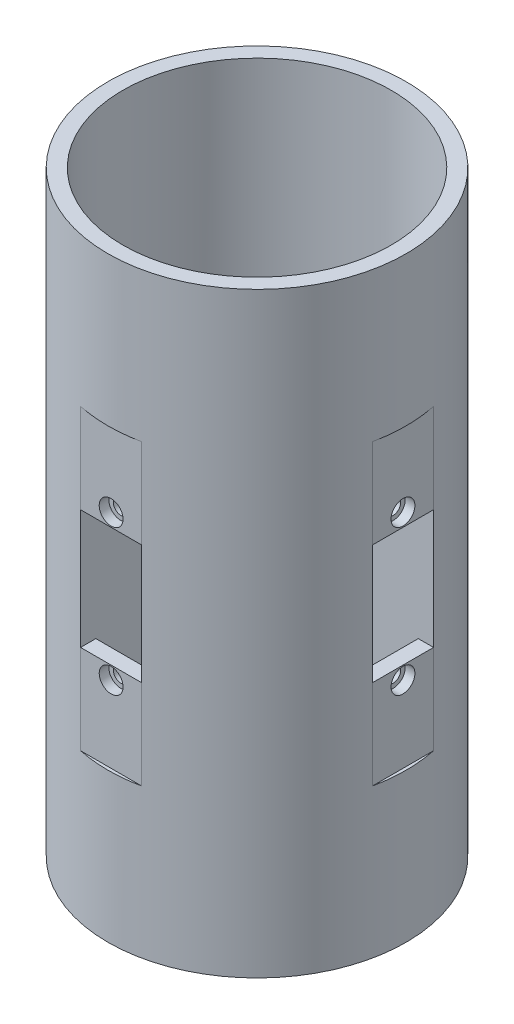
SolidWorks part; units mm, degrees
ref_plane "前视基准面" through (0, 0, 0) normal (0, 0, 1) x (1, 0, 0)
ref_plane "上视基准面" through (0, 0, 0) normal (0, 1, 0) x (1, 0, 0)
ref_plane "右视基准面" through (0, 0, 0) normal (1, 0, 0) x (0, 0, -1)
other "Configuration Table"
sketch "草图1" plane through (0, 0, 0) normal (0, 1, 0) x (1, 0, 0)
  circle A0 centre (0, 0) radius 20
  circle A1 centre (0, 0) radius 18
  dimension "D1" = 40
  dimension "D2" = 36
extrude "凸台-拉伸1" add sketch "草图1" along normal blind 80
sketch "草图2" plane through (0, 0, 0) normal (0, 1, 0) x (1, 0, 0)
  line L0 (-1000, 0) -> (49000, 0) construction
  line L1 (0, -1000) -> (0, 49000) construction
  line L2 (17.5268, -4.1) -> (17.5268, 4.1)
  line L3 (17.5268, 4.1) -> (-17.5268, 4.1) construction
  line L4 (17.5268, -4.1) -> (-17.5268, -4.1) construction
  line L5 (19.5752, 4.1) -> (19.5752, -4.1)
  line L6 (-17.5268, 4.1) -> (-17.5268, -4.1)
  line L7 (-19.5752, 4.1) -> (-19.5752, -4.1)
  line L8 (17.5268, 4.1) -> (19.5752, 4.1)
  line L9 (19.5752, -4.1) -> (17.5268, -4.1)
  line L10 (-19.5752, 4.1) -> (-17.5268, 4.1)
  line L11 (-17.5268, -4.1) -> (-19.5752, -4.1)
  line L12 (-707.1068, -707.1068) -> (34648.2323, 34648.2323) construction
  line L13 (707.1068, -707.1068) -> (-34648.2323, 34648.2323) construction
  line L14 (-4.1, -17.5268) -> (-4.1, -19.5752)
  line L15 (-4.1, -19.5752) -> (4.1, -19.5752)
  line L16 (4.1, -17.5268) -> (-4.1, -17.5268)
  line L17 (4.1, -19.5752) -> (4.1, -17.5268)
  line L18 (-4.1, 19.5752) -> (-4.1, 17.5268)
  line L19 (-4.1, 19.5752) -> (4.1, 19.5752)
  line L20 (4.1, 17.5268) -> (4.1, 19.5752)
  line L21 (-4.1, 17.5268) -> (4.1, 17.5268)
  circle A0 centre (0, 0) radius 18
  circle A1 centre (0, 0) radius 20
  point P11 (17.5268, 0)
  dimension "D1" = 36
  dimension "D2" = 40
  dimension "D3" = 8.2
  dimension "D4" = 8.2
  dimension "D5" = 8.2
extrude "凸台-拉伸2" add sketch "草图2" along normal blind 30 from offset 25 contours A0 L20 L19 L18 | L15 L17 L16 L14 | L7 L11 L6 L10 | L9 L2 L8 L5
sketch "草图3" plane through (0, 0, 0) normal (0, 1, 0) x (1, 0, 0)
  line L0 (-4.1, 19.5752) -> (4.1, 19.5752) construction
  line L1 (-4.1, 19.5752) -> (4.1, 19.5752)
  line L2 (-4.1, -19.5752) -> (4.1, -19.5752) construction
  line L3 (19.5752, 4.1) -> (19.5752, -4.1) construction
  line L4 (-19.5752, 4.1) -> (-19.5752, -4.1) construction
  line L5 (-4.1, -19.5752) -> (4.1, -19.5752)
  line L6 (19.5752, 4.1) -> (19.5752, -4.1)
  line L7 (-19.5752, 4.1) -> (-19.5752, -4.1)
  circle A0 centre (0, 0) radius 20 construction
  circle A1 centre (0, 0) radius 20
extrude "切除-拉伸1" cut sketch "草图3" along normal blind 40 from offset 20 contours L7 A1 | L5 A1 | L6 A1 | L1 A1
sketch "草图4" plane through (0, 0, 0) normal (0, 0, 1) x (1, 0, 0)
  line L0 (4.1, 28.5) -> (4.1, 51.5)
  line L1 (-4.1, 28.5) -> (-4.1, 51.5)
  line L2 (-4.1, 51.5) -> (4.1, 51.5)
  line L3 (4.1, 28.5) -> (-4.1, 28.5)
  line L4 (-4.1, 20) -> (4.1, 20)
  line L5 (4.1, 20) -> (4.1, 60)
  line L6 (4.1, 60) -> (-4.1, 60)
  line L7 (-4.1, 60) -> (-4.1, 20)
  line L8 (-4.1, 20) -> (4.1, 20) construction
  line L9 (4.1, 20) -> (4.1, 60) construction
  line L10 (4.1, 60) -> (-4.1, 60) construction
  line L11 (-4.1, 60) -> (-4.1, 20) construction
  line L12 (4.1, 51.5) -> (-4.1, 28.5) construction
  line L13 (-4.1, 51.5) -> (4.1, 28.5) construction
  line L14 (0, 49.75) -> (0, 30.25) construction
  line L15 (4.1, 32) -> (4.1, 48)
  line L16 (4.1, 48) -> (-4.1, 48)
  line L17 (4.1, 32) -> (-4.1, 32)
  line L18 (-4.1, 32) -> (-4.1, 48)
  circle A0 centre (0, 49.75) radius 1
  circle A1 centre (0, 30.25) radius 1
  point P7 (4.1, 40)
  point P10 (-4.1, 40)
  point P13 (0, 40)
  point P18 (4.1, 40)
  dimension "D5" = 2
  dimension "D6" = 2
  dimension "D2" = 23
  dimension "D3" = 23
  dimension "D4" = 19.5
  dimension "D1" = 0
extrude "切除-拉伸3" cut sketch "草图4" against normal blind 30 and the other way blind 30 contours L17 L0 L16 L1 | A0 | A1
sketch "草图5" plane through (0, 0, 0) normal (1, 0, 0) x (0, 0, -1)
  line L4 (4.1, 60) -> (-4.1, 20) construction
  line L5 (-4.1, 20) -> (4.1, 20) construction
  line L6 (4.1, 20) -> (-4.1, 60) construction
  line L7 (4.1, 32) -> (4.1, 48)
  line L8 (-4.1, 20) -> (4.1, 20)
  line L9 (4.1, 20) -> (4.1, 60)
  line L10 (4.1, 60) -> (-4.1, 60)
  line L11 (-4.1, 60) -> (-4.1, 20)
  line L12 (-4.1, 20) -> (4.1, 20) construction
  line L13 (4.1, 20) -> (4.1, 60) construction
  line L14 (4.1, 60) -> (-4.1, 60) construction
  line L15 (-4.1, 60) -> (-4.1, 20) construction
  line L16 (4.1, 48) -> (-4.1, 48)
  line L17 (-4.1, 48) -> (-4.1, 32)
  line L18 (-4.1, 32) -> (4.1, 32)
  line L19 (0, 49.75) -> (0, 30.25) construction
  circle A0 centre (0, 49.75) radius 1
  circle A1 centre (0, 30.25) radius 1
  point P5 (4.1, 40)
  point P13 (0, 40)
  dimension "D4" = 2
  dimension "D5" = 2
  dimension "D2" = 16
  dimension "D3" = 19.5
  dimension "D1" = 0
extrude "切除-拉伸4" cut sketch "草图5" against normal blind 30 and the other way blind 30 contours A0 | L18 L7 L16 L17 | A1
sketch "草图6" plane through (0, 0, 0) normal (0, 1, 0) x (1, 0, 0)
  line L0 (17.5268, -4.1) -> (17.5268, 4.1) construction
  line L1 (17.5268, -4.1) -> (17.5268, 4.1)
  line L2 (4.1, -17.5268) -> (-4.1, -17.5268) construction
  line L3 (-4.1, 17.5268) -> (4.1, 17.5268) construction
  line L4 (-17.5268, 4.1) -> (-17.5268, -4.1) construction
  line L5 (4.1, -17.5268) -> (-4.1, -17.5268)
  line L6 (-4.1, 17.5268) -> (4.1, 17.5268)
  line L7 (-17.5268, 4.1) -> (-17.5268, -4.1)
  line L8 (-4.1, 17.5268) -> (-4.1, 4.1)
  line L9 (4.1, 17.5268) -> (4.1, 4.1)
  line L10 (17.5268, 4.1) -> (4.1, 4.1)
  line L11 (-17.5268, -4.1) -> (-4.1, -4.1)
  line L12 (-4.1, -4.1) -> (-4.1, -17.5268)
  line L13 (-4.1, 4.1) -> (-17.5268, 4.1)
  line L14 (4.1, -4.1) -> (4.1, -17.5268)
  line L15 (4.1, -4.1) -> (17.5268, -4.1)
  line L16 (17.1067, 5.6) -> (5.6, 5.6)
  line L17 (5.6, 17.1067) -> (5.6, 5.6)
  line L18 (5.6, -5.6) -> (5.6, -17.1067)
  line L19 (5.6, -5.6) -> (17.1067, -5.6)
  line L20 (-5.6, 17.1067) -> (-5.6, 5.6)
  line L21 (-5.6, 5.6) -> (-17.1067, 5.6)
  line L22 (-17.1067, -5.6) -> (-5.6, -5.6)
  line L23 (-5.6, -5.6) -> (-5.6, -17.1067)
  line L25 (-5.6, 5.6) -> (-17.5268, 5.6) construction
  line L26 (-17.5268, -5.6) -> (-5.6, -5.6) construction
  line L27 (5.6, 17.5268) -> (5.6, 5.6) construction
  line L28 (-5.6, 17.5268) -> (-5.6, 5.6) construction
  line L29 (-5.6, -5.6) -> (-5.6, -17.5268) construction
  line L30 (5.6, -5.6) -> (5.6, -17.5268) construction
  line L31 (17.5268, 5.6) -> (5.6, 5.6) construction
  line L32 (5.6, -5.6) -> (17.5268, -5.6) construction
  circle A0 centre (0, 0) radius 18 construction
  circle A1 centre (0, 0) radius 18
  dimension "D1" = 1.5
  dimension "D2" = 1.5
  dimension "D3" = 1.5
  dimension "D4" = 1.5
extrude "凸台-拉伸3" add sketch "草图6" along normal blind 30 from offset 25 contours L8 A1 L20 L21 L13 | L10 A1 L16 L17 L9 | L14 A1 L18 L19 L15 | L11 A1 L22 L23 L12
sketch "草图7" plane through (0, 0, 0) normal (0, 1, 0) x (1, 0, 0)
  line L0 (5.6, -5.6) -> (17.1067, -5.6) construction
  line L1 (5.6, -5.6) -> (5.6, -17.1067) construction
  line L2 (-5.6, -5.6) -> (-5.6, -17.1067) construction
  line L3 (-17.1067, -5.6) -> (-5.6, -5.6) construction
  line L4 (-5.6, 5.6) -> (-17.1067, 5.6) construction
  line L5 (-5.6, 17.1067) -> (-5.6, 5.6) construction
  line L6 (17.1067, 5.6) -> (5.6, 5.6) construction
  line L7 (5.6, 17.1067) -> (5.6, 5.6) construction
  line L8 (5.6, -5.6) -> (17.1067, -5.6)
  line L9 (5.6, -5.6) -> (5.6, -17.1067)
  line L10 (-5.6, -5.6) -> (-5.6, -17.1067)
  line L11 (-17.1067, -5.6) -> (-5.6, -5.6)
  line L12 (-5.6, 5.6) -> (-17.1067, 5.6)
  line L13 (-5.6, 17.1067) -> (-5.6, 5.6)
  line L14 (17.1067, 5.6) -> (5.6, 5.6)
  line L15 (5.6, 17.1067) -> (5.6, 5.6)
  line L16 (-1000, 0) -> (49000, 0) construction
  line L17 (0, -1000) -> (0, 49000) construction
  line L18 (-707.1068, -707.1068) -> (34648.2323, 34648.2323) construction
  line L19 (707.1068, -707.1068) -> (-34648.2323, 34648.2323) construction
  line L20 (-12.7279, 12.7279) -> (-5.6, 5.6)
  line L21 (-10.755, 10.755) -> (-7.573, 7.573) construction
  line L22 (-10.0478, 11.4621) -> (-6.8659, 8.2801)
  line L23 (-11.4621, 10.0478) -> (-8.2801, 6.8659)
  line L24 (10.755, 10.755) -> (7.573, 7.573) construction
  line L25 (10.0478, 11.4621) -> (6.8659, 8.2801)
  line L26 (11.4621, 10.0478) -> (8.2801, 6.8659)
  line L27 (10.755, -10.755) -> (7.573, -7.573) construction
  line L28 (10.0478, -11.4621) -> (6.8659, -8.2801)
  line L29 (11.4621, -10.0478) -> (8.2801, -6.8659)
  line L30 (-10.755, -10.755) -> (-7.573, -7.573) construction
  line L31 (-10.0478, -11.4621) -> (-6.8659, -8.2801)
  line L32 (-11.4621, -10.0478) -> (-8.2801, -6.8659)
  circle A0 centre (0, 0) radius 18 construction
  circle A1 centre (0, 0) radius 18
  arc A2 (-10.0478, 11.4621) -> (-11.4621, 10.0478) centre (-10.755, 10.755) ccw
  arc A3 (-8.2801, 6.8659) -> (-6.8659, 8.2801) centre (-7.573, 7.573) ccw
  arc A4 (10.0478, 11.4621) -> (11.4621, 10.0478) centre (10.755, 10.755) cw
  arc A5 (8.2801, 6.8659) -> (6.8659, 8.2801) centre (7.573, 7.573) cw
  arc A6 (10.0478, -11.4621) -> (11.4621, -10.0478) centre (10.755, -10.755) ccw
  arc A7 (8.2801, -6.8659) -> (6.8659, -8.2801) centre (7.573, -7.573) ccw
  arc A8 (-10.0478, -11.4621) -> (-11.4621, -10.0478) centre (-10.755, -10.755) cw
  arc A9 (-8.2801, -6.8659) -> (-6.8659, -8.2801) centre (-7.573, -7.573) cw
  point P26 (-9.164, 9.164)
  point P33 (9.164, 9.164)
  point P40 (9.164, -9.164)
  point P47 (-9.164, -9.164)
  dimension "D1" = 4.5
  dimension "D2" = 1
extrude "凸台-拉伸4" add sketch "草图7" along normal blind 2 from offset 39 contours L14 A1 L15 L26 A5 L25 A4 | L9 A1 L8 A7 L29 A6 L28 | L11 A1 L10 L32 A9 L31 A8 | A3 L20 L13 A1 A2 L22 | A3 L23 A2 L20 A1 L12
sketch "草图8" plane through (0, 0, 0) normal (0, 0, 1) x (1, 0, 0)
  circle A0 centre (0, 49.75) radius 1.6
  circle A1 centre (0, 30.25) radius 1.6
  dimension "D1" = 3.2
  dimension "D2" = 3.2
extrude "切除-拉伸5" cut sketch "草图8" against normal blind 1.3 from surface contours A1 | A0
sketch "草图9" plane through (0, 0, 0) normal (0, 0, 1) x (1, 0, 0)
  circle A0 centre (0, 49.75) radius 1.6 construction
  circle A1 centre (0, 49.75) radius 1.6
  circle A2 centre (0, 30.25) radius 1.6 construction
  circle A3 centre (0, 30.25) radius 1.6
extrude "切除-拉伸6" cut sketch "草图9" along normal blind 1.3 from surface
sketch "草图10" plane through (0, 0, 0) normal (1, 0, 0) x (0, 0, -1)
  circle A0 centre (0, 49.75) radius 1.6
  circle A1 centre (0, 30.25) radius 1.6
  dimension "D1" = 3.2
  dimension "D2" = 3.2
extrude "切除-拉伸7" cut sketch "草图10" along normal blind 1.3 from surface
sketch "草图11" plane through (0, 0, 0) normal (1, 0, 0) x (0, 0, -1)
  circle A0 centre (0, 30.25) radius 1.6 construction
  circle A1 centre (0, 49.75) radius 1.6
  circle A2 centre (0, 49.75) radius 1.6
  circle A3 centre (0, 30.25) radius 1.6
  dimension "D1" = 0
extrude "切除-拉伸8" cut sketch "草图11" against normal blind 1.3 from surface
